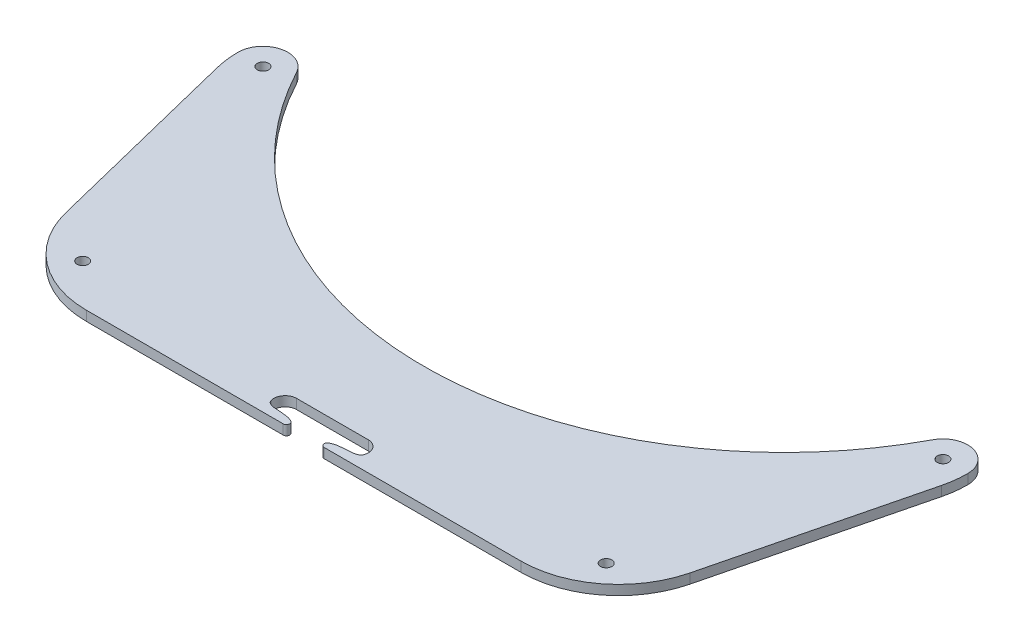
SolidWorks part; units mm, degrees
ref_plane "前视基准面" through (0, 0, 0) normal (0, 0, 1) x (1, 0, 0)
ref_plane "上视基准面" through (0, 0, 0) normal (0, 1, 0) x (1, 0, 0)
ref_plane "右视基准面" through (0, 0, 0) normal (1, 0, 0) x (0, 0, -1)
sketch "草图1" plane through (0, 0, 0) normal (0, 1, 0) x (1, 0, 0)
  line L3 (-66.7806, 154.594) -> (66.7806, 154.594)
  line L4 (-95.8987, 131.8145) -> (-111.2655, 69.8447)
  line L5 (-96.25, 148.3486) -> (-96.25, 83.3486) construction
  line L6 (95.8987, 131.8145) -> (111.2655, 69.8447)
  line L7 (95.8987, -6.5662) -> (111.2655, 55.4037)
  line L9 (-95.8987, -6.5662) -> (-111.2655, 55.4037)
  line L10 (137.9048, 62.6242) -> (-113.2043, 62.6242) construction
  line L12 (-66.7806, -29.3457) -> (66.7806, -29.3457)
  line L20 (0, 9.3997) -> (0, 129.3997) construction
  arc A0 (95.8987, -6.5662) -> (66.7806, -29.3457) centre (66.7806, 0.6543) cw
  arc A1 (-66.7806, -29.3457) -> (-95.8987, -6.5662) centre (-66.7806, 0.6543) cw
  arc A2 (111.2655, 55.4037) -> (111.2655, 69.8447) centre (82.1474, 62.6242) ccw
  arc A3 (-111.2655, 69.8447) -> (-111.2655, 55.4037) centre (-82.1474, 62.6242) ccw
  arc A6 (-66.7806, 154.594) -> (-95.8987, 131.8145) centre (-66.7806, 124.594) ccw
  arc A7 (95.8987, 131.8145) -> (66.7806, 154.594) centre (66.7806, 124.594) ccw
  point P16 (-90.25, 154.594)
  point P18 (90.25, -29.3457)
  point P24 (-90.25, -29.3457)
  point P26 (0, 62.6242)
  point P27 (90.25, 154.594)
  point P28 (113.2043, 62.6242)
  dimension "D5" = 30
  dimension "D6" = 30
extrude "凸台-拉伸1" add sketch "草图1" along normal blind 3
sketch "草图2" plane through (0, 3, 0) normal (0, 1, 0) x (1, 0, 0)
  line L0 (0, 81.8031) -> (0, 20.2944) construction
  line L7 (111.2655, 69.8447) -> (95.8987, 131.8145)
  line L8 (66.7806, 154.594) -> (-66.7806, 154.594)
  line L9 (-95.8987, 131.8145) -> (-111.2655, 69.8447)
  line L10 (-111.2655, 55.4037) -> (-95.8987, -6.5662)
  line L11 (-66.7806, -29.3457) -> (66.7806, -29.3457)
  line L12 (95.8987, -6.5662) -> (111.2655, 55.4037)
  line L13 (111.2655, 69.8447) -> (95.8987, 131.8145)
  line L14 (66.7806, 154.594) -> (-66.7806, 154.594)
  line L15 (-95.8987, 131.8145) -> (-111.2655, 69.8447)
  arc A0 (-97.767, 66.2204) -> (-112.1474, 62.6242) centre (-104.5075, 62.6242) ccw
  arc A1 (97.767, 66.2204) -> (112.1474, 62.6242) centre (104.5075, 62.6242) cw
  arc A2 (-97.767, 66.2204) -> (97.767, 66.2204) centre (0, 118.3821) ccw
  arc A9 (95.8987, 131.8145) -> (66.7806, 154.594) centre (66.7806, 124.594) ccw
  arc A10 (-66.7806, 154.594) -> (-95.8987, 131.8145) centre (-66.7806, 124.594) ccw
  arc A11 (-111.2655, 69.8447) -> (-111.2655, 55.4037) centre (-82.1474, 62.6242) ccw
  arc A12 (-95.8987, -6.5662) -> (-66.7806, -29.3457) centre (-66.7806, 0.6543) ccw
  arc A13 (66.7806, -29.3457) -> (95.8987, -6.5662) centre (66.7806, 0.6543) ccw
  arc A14 (111.2655, 55.4037) -> (111.2655, 69.8447) centre (82.1474, 62.6242) ccw
  arc A15 (95.8987, 131.8145) -> (66.7806, 154.594) centre (66.7806, 124.594) ccw
  arc A16 (-66.7806, 154.594) -> (-95.8987, 131.8145) centre (-66.7806, 124.594) ccw
  arc A17 (-111.2655, 69.8447) -> (-112.1474, 62.6242) centre (-82.1474, 62.6242) ccw
  arc A20 (112.1474, 62.6242) -> (111.2655, 69.8447) centre (82.1474, 62.6242) ccw
  dimension "D1" = 0
extrude "切除-拉伸1" cut sketch "草图2" against normal blind 10
sketch "草图3" plane through (0, 3, 0) normal (0, 1, 0) x (1, 0, 0)
  circle A0 centre (-80.4502, -16.819) radius 1.75 construction
  circle A1 centre (-104.5075, 62.6242) radius 1.75 construction
  circle A2 centre (104.5075, 62.6242) radius 1.75 construction
  circle A3 centre (80.4502, -16.819) radius 1.75 construction
  circle A4 centre (-80.4502, -16.819) radius 1.75
  circle A5 centre (-104.5075, 62.6242) radius 1.75
  circle A6 centre (104.5075, 62.6242) radius 1.75
  circle A7 centre (80.4502, -16.819) radius 1.75
extrude "切除-拉伸2" cut sketch "草图3" against normal blind 10
sketch "草图4" plane through (0, 3, 0) normal (0, 1, 0) x (1, 0, 0)
  line L0 (11.0166, -20.5139) -> (-11.0166, -20.5139) construction
  line L1 (11.0166, -20.5139) -> (-11.0166, -20.5139)
  line L2 (6.2934, -29.3457) -> (-6.2934, -29.3457)
  arc A0 (5.8046, -27.4733) -> (6.2934, -29.3457) centre (6.2934, -28.3457) ccw construction
  arc A1 (-11.0166, -20.5139) -> (-14.3785, -24.9877) centre (-11.0166, -24.0139) ccw construction
  arc A2 (14.3785, -24.9877) -> (11.0166, -20.5139) centre (11.0166, -24.0139) ccw construction
  arc A3 (-6.2934, -29.3457) -> (-5.8046, -27.4733) centre (-6.2934, -28.3457) ccw construction
  arc A4 (5.8046, -27.4733) -> (6.2934, -29.3457) centre (6.2934, -28.3457) ccw
  arc A5 (-6.2934, -29.3457) -> (-5.8046, -27.4733) centre (-6.2934, -28.3457) ccw
  arc A6 (14.3785, -24.9877) -> (11.0166, -20.5139) centre (11.0166, -24.0139) ccw
  arc A7 (-11.0166, -20.5139) -> (-14.3785, -24.9877) centre (-11.0166, -24.0139) ccw
  spline S0 degree 3 poles (2760.8348, 1159.3656) (-7.2239, -47.3403) (1.4545, -25.8897) (22.3045, -27.8983) (63.8711, -2.609) (-2373.261, 1790.5881) knots -1.763167 -1.763167 -1.763167 -1.763167 0.031904 0.50327 4.099766 4.099766 4.099766 4.099766 only from (5.8046, -27.4733) to (14.3785, -24.9877) construction
  spline S1 degree 3 poles (2373.2568, 1790.5851) (-63.8711, -2.6091) (-22.3045, -27.8983) (-1.4545, -25.8897) (7.2239, -47.3402) (-2760.8232, 1159.3606) knots -3.32237 -3.32237 -3.32237 -3.32237 0.274124 0.74549 2.540558 2.540558 2.540558 2.540558 only from (-14.3785, -24.9877) to (-5.8046, -27.4733) construction
  spline S2 degree 3 poles (-14.3785, -24.9877) (-14.0507, -26.1193) (-10.4893, -26.7601) (-7.7247, -26.4938) (-5.9045, -27.4173) (-5.8046, -27.4733) knots 0 0 0 0 0.274124 0.74549 0.777394 0.777394 0.777394 0.777394
  spline S3 degree 3 poles (5.8046, -27.4733) (5.9045, -27.4173) (7.7247, -26.4938) (10.4893, -26.7601) (14.0507, -26.1193) (14.3785, -24.9877) knots 0 0 0 0 0.031904 0.50327 0.777394 0.777394 0.777394 0.777394
  point P3 (5.3259, -28.5983)
extrude "切除-拉伸3" cut sketch "草图4" against normal blind 10
